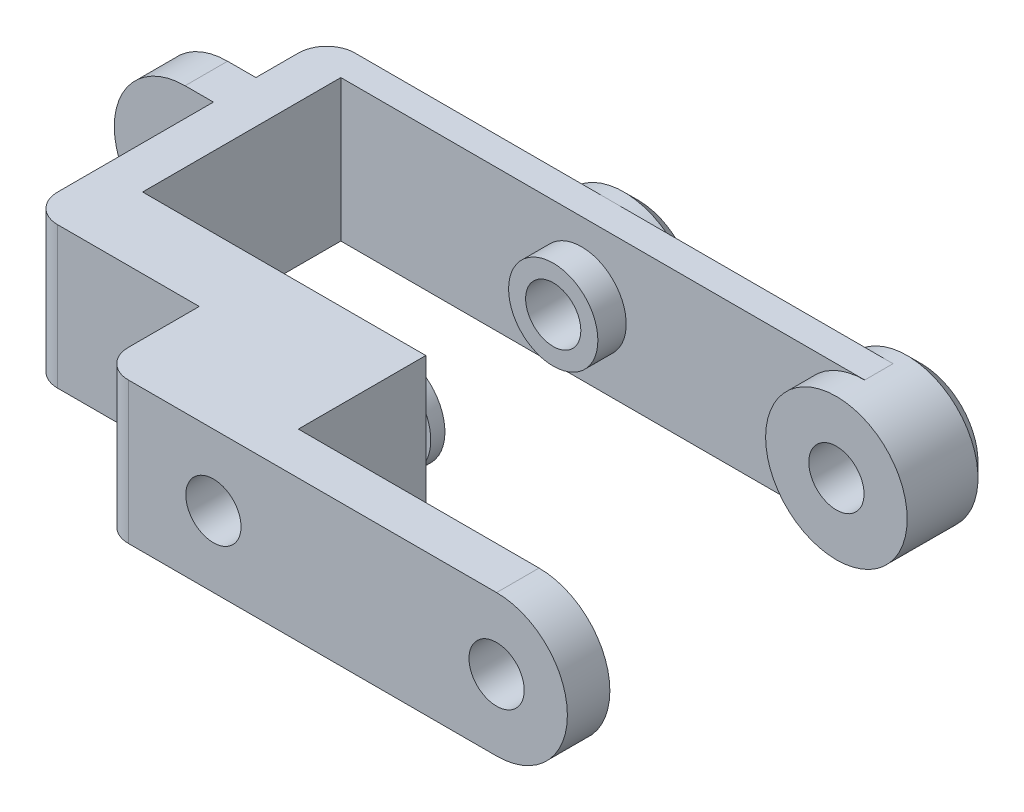
SolidWorks part; units mm, degrees
ref_plane "Alzado" through (0, 0, 0) normal (0, 0, 1) x (1, 0, 0)
ref_plane "Planta" through (0, 0, 0) normal (0, 1, 0) x (1, 0, 0)
ref_plane "Vista lateral" through (0, 0, 0) normal (1, 0, 0) x (0, 0, -1)
sketch "Croquis1" plane through (0, 0, 0) normal (0, 0, 1) x (1, 0, 0)
  line L0 (0, 0) -> (50000, 0) construction
  line L1 (-22, 0) -> (20, 0) construction
  line L2 (-22, 5) -> (20, 5)
  line L3 (-22, -5) -> (20, -5)
  circle A0 centre (0, 0) radius 1.95
  circle A1 centre (20, 0) radius 1.95
  circle A2 centre (-22, 0) radius 1
  arc A3 (-22, 5) -> (-22, -5) centre (-22, 0) ccw
  arc A4 (20, -5) -> (20, 5) centre (20, 0) ccw
  point P7 (-1, 0)
  dimension "D1" = 3.9
  dimension "D3" = 2
  dimension "D5" = 5
  dimension "D2" = 20
  dimension "D4" = 22
extrude "Saliente-Extruir1" add sketch "Croquis1" along normal mid plane 28
sketch "Croquis2" plane through (0, 5, 0) normal (0, 1, 0) x (1, 0, 0)
  line L0 (25, 12) -> (-17, 12)
  line L1 (25, -14) -> (25, 14) construction
  line L2 (-17, 12) -> (-17, -2)
  line L3 (-17, -2) -> (3, -2)
  line L4 (3, -2) -> (3, -11)
  line L5 (3, -11) -> (25, -11)
  line L6 (25, -11) -> (25, 12)
  line L7 (20, 14) -> (-22, 14) construction
  line L8 (-27, 14) -> (-20, 14)
  line L9 (-27, 14) -> (-27, 9)
  line L10 (-27, 9) -> (-20, 9)
  line L11 (-20, 14) -> (-20, 9)
  line L12 (-27, -14) -> (-18.2, -14)
  line L13 (-27, -14) -> (-27, 6)
  line L14 (-27, 6) -> (-20, 6)
  line L15 (-20, -7) -> (-20, 6)
  line L16 (20, -14) -> (-22, -14) construction
  line L17 (20, -14) -> (20, 14) construction
  line L18 (-18.2, -14) -> (-8, -14)
  line L20 (-20, -7) -> (-8, -7)
  line L21 (-8, -14) -> (-8, -7)
  point P28 (-23.5, 14)
  dimension "D1" = 2
  dimension "D2" = 3
  dimension "D3" = 17
  dimension "D4" = 3
  dimension "D5" = 5
  dimension "D6" = 11
  dimension "D7" = 17
  dimension "D8" = 5
  dimension "D9" = 3
  dimension "D10" = 14
extrude "Cortar-Extruir1" cut sketch "Croquis2" against normal through all both and the other way through all
fillet "Redondeo1" radius 2 3 edges at (-8, 0, 14) (-20, 0, 7) (-20, 0, -14)
sketch "Croquis3" plane through (0, 0, -12) normal (0, 0, 1) x (1, 0, 0)
  circle A0 centre (20, 0) radius 5
  circle A1 centre (20, 0) radius 1.95
  circle A2 centre (0, 0) radius 1.95
  circle A3 centre (0, 0) radius 3.153
extrude "Saliente-Extruir2" add sketch "Croquis3" along normal blind 2
sketch "Croquis4" plane through (0, 0, 2) normal (0, 0, -1) x (-1, 0, 0)
  circle A0 centre (0, 0) radius 1.95
  circle A1 centre (0, 0) radius 3.35
  point P4 (0, 0)
  dimension "D1" = 1.4
extrude "Saliente-Extruir3" add sketch "Croquis4" along normal blind 1
sketch "Croquis5" plane through (0, 0, -14) normal (0, 0, -1) x (-1, 0, 0)
  circle A0 centre (-20, 0) radius 1.95
  circle A1 centre (-20, 0) radius 5
  circle A2 centre (0, 0) radius 1.95
  circle A3 centre (0, 0) radius 5
extrude "Saliente-Extruir4" add sketch "Croquis5" along normal blind 2
chamfer "Chaflán1" distance 1 angle 45 2 edges at (15, 0, -16) (-5, 0, -16)
